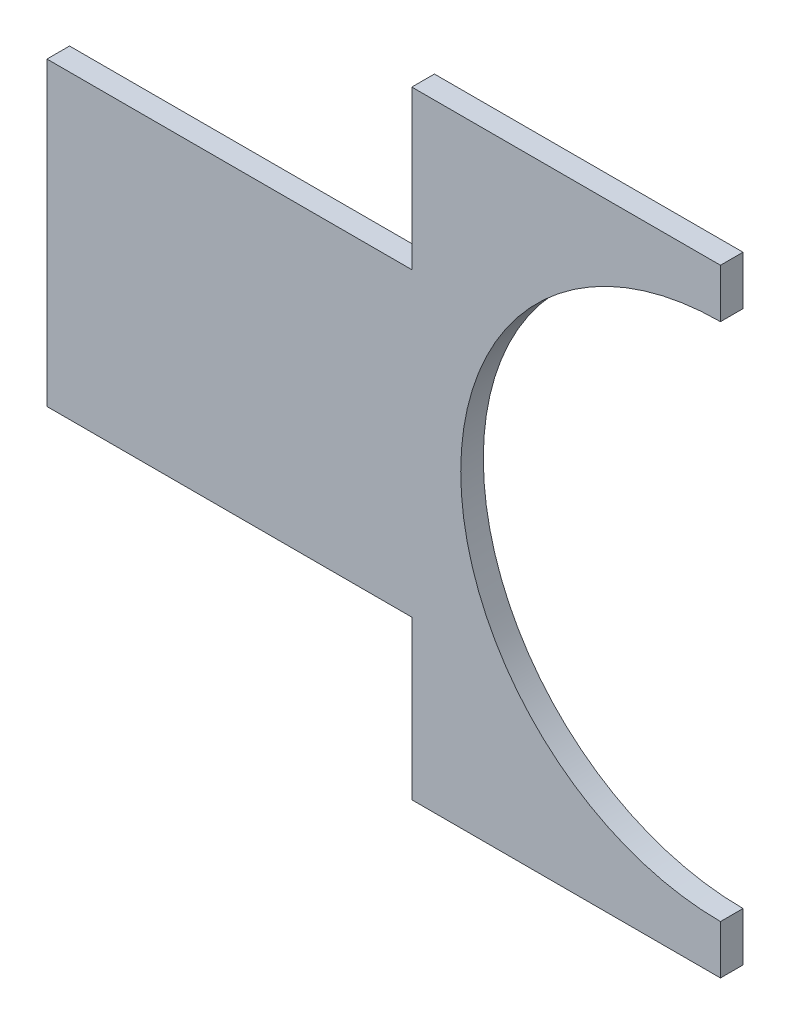
SolidWorks part; units mm, degrees
ref_plane "Спереди" through (0, 0, 0) normal (0, 0, 1) x (1, 0, 0)
ref_plane "Сверху" through (0, 0, 0) normal (0, 1, 0) x (1, 0, 0)
ref_plane "Справа" through (0, 0, 0) normal (1, 0, 0) x (0, 0, -1)
other "Configuration Table"
sketch "Эскиз1" plane through (0, 0, 0) normal (0, 0, 1) x (1, 0, 0)
  line L1 (55, 40) -> (-55, 40)
  line L2 (55, 40) -> (55, -40)
  line L3 (55, -40) -> (-55, -40)
  line L4 (-55, 40) -> (-55, -40)
  line L5 (55, 40) -> (-55, -40) construction
  line L6 (55, -40) -> (-55, 40) construction
  point P0 (0, 0)
  dimension "D1" = 80
  dimension "D2" = 110
extrude "Бобышка-Вытянуть1" add sketch "Эскиз1" along normal blind 6
sketch "Эскиз2" plane through (0, 0, 6) normal (0, 0, 1) x (1, 0, 0)
  line L0 (55, -40) -> (55, 40) construction
  line L2 (42, 82.05) -> (124.05, 82.05)
  line L3 (42, 82.05) -> (42, -82.05)
  line L4 (42, -82.05) -> (124.05, -82.05)
  line L5 (124.05, 82.05) -> (124.05, -82.05)
  circle A0 centre (124.05, 0) radius 69.05
  point P9 (124.05, 69.05)
  point P10 (124.05, -69.05)
  point P11 (42, 0)
  point P12 (55, 0)
  line M6 (55, -40) -> (55, 40)
  dimension "D1" = 138.1
  dimension "D4" = 13
  dimension "D5" = 13
  dimension "D2" = 13
extrude "Бобышка-Вытянуть2" add sketch "Эскиз2" against normal up to surface (6 mm away) contours A0 L5 L2 L3 | A0 L3 L4 L5 M6
equation "\"D4@Эскиз2\"=\"D2@Эскиз2\""
equation "\"D5@Эскиз2\"=\"D2@Эскиз2\""
